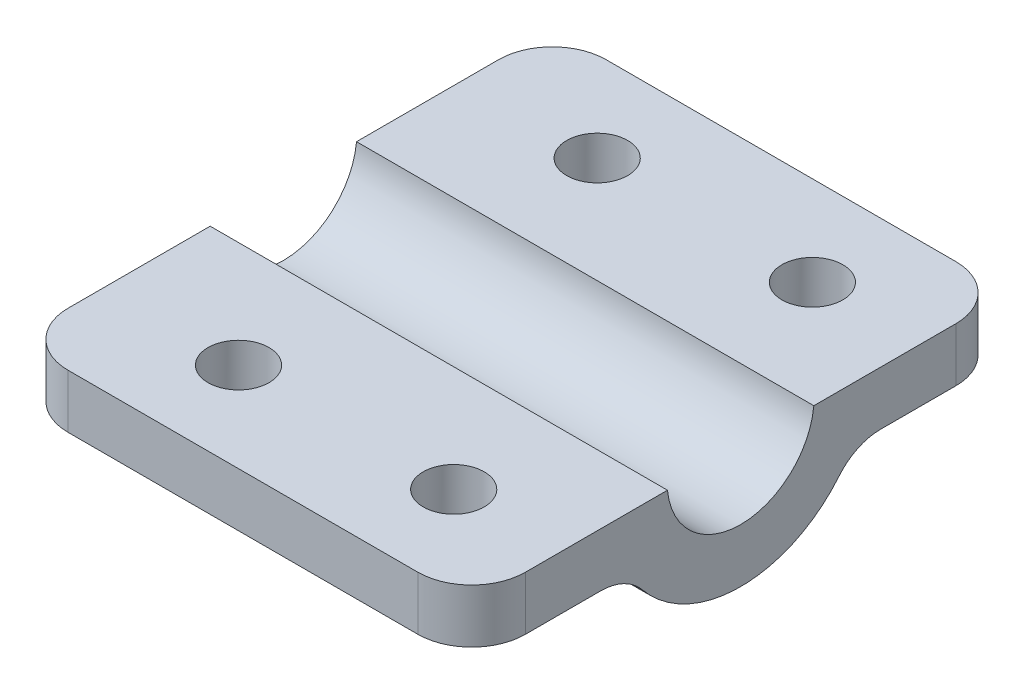
SolidWorks part; units mm, degrees
ref_plane "Front" through (0, 0, 0) normal (0, 0, 1) x (1, 0, 0)
ref_plane "Top" through (0, 0, 0) normal (0, 1, 0) x (1, 0, 0)
ref_plane "Right" through (0, 0, 0) normal (1, 0, 0) x (0, 0, -1)
sketch "Sketch1" plane through (0, 0, 0) normal (1, 0, 0) x (0, 0, -1)
  line L2 (4.0804, -0.4) -> (15, -0.4)
  line L3 (15, -0.4) -> (15, -3.4)
  line L4 (15, -3.4) -> (6.233, -3.4)
  line L5 (-4.0804, -0.4) -> (-15, -0.4)
  line L6 (-15, -0.4) -> (-15, -3.4)
  line L7 (-15, -3.4) -> (-6.233, -3.4)
  line L9 (4.1, 0) -> (-4.1, 0) construction
  arc A0 (6.233, -3.4) -> (-6.233, -3.4) centre (0, 0) cw
  circle A1 centre (0, 0) radius 4
  circle A2 centre (0, 0) radius 4 construction
  arc A3 (4.0804, -0.4) -> (-4.0804, -0.4) centre (0, 0) cw
  dimension "D2" = 0.1
  dimension "D3" = 15
  dimension "D5" = 3
  dimension "D6" = 3
  dimension "D4" = 15
  dimension "D7" = 0.4
  dimension "D1" = 0
extrude "Boss-Extrude1" add sketch "Sketch1" against normal up to surface (25.5 mm away)
sketch "Sketch2" plane through (0, 0, 0) normal (0, 1, 0) x (1, 0, 0)
  circle A0 centre (-6, -10) radius 1.7 construction
  circle A1 centre (-18, -10) radius 1.7 construction
  circle A2 centre (-6, 10) radius 1.7 construction
  circle A3 centre (-18, 10) radius 1.7 construction
  circle A4 centre (-6, -10) radius 1.7
  circle A5 centre (-18, -10) radius 1.7
  circle A6 centre (-6, 10) radius 1.7
  circle A7 centre (-18, 10) radius 1.7
extrude "Cut-Extrude1" cut sketch "Sketch2" against normal through all
sketch "Sketch4" plane through (0, -3.4, 0) normal (0, -1, 0) x (1, 0, 0)
  circle A0 centre (-18, -10) radius 2.85
  circle A1 centre (-18, 10) radius 2.85
  circle A2 centre (-6, 10) radius 2.85
  circle A3 centre (-6, -10) radius 2.85
  circle A4 centre (-6, -10) radius 1.7 construction
  circle A5 centre (-18, -10) radius 1.7 construction
  circle A6 centre (-18, 10) radius 1.7 construction
  circle A7 centre (-6, 10) radius 1.7 construction
  dimension "D1" = 5.7
  dimension "D2" = 5.7
  dimension "D3" = 5.7
  dimension "D4" = 5.7
fillet "Fillet1" radius 3 6 edges at (-25.5, -1.9, 15) (-25.5, -1.9, -15) (0, -1.9, 15) (0, -1.9, -15) (-12.75, -3.4, 6.233) (-12.75, -3.4, -6.233)
extrude "Cut-Extrude2" cut sketch "Sketch4" along normal through all
equation "\"D4@Sketch1\"=\"D3@Sketch1\""
equation "\"D2@Sketch4\"=\"D1@Sketch4\""
equation "\"D3@Sketch4\"=\"D1@Sketch4\""
equation "\"D4@Sketch4\"=\"D1@Sketch4\""
